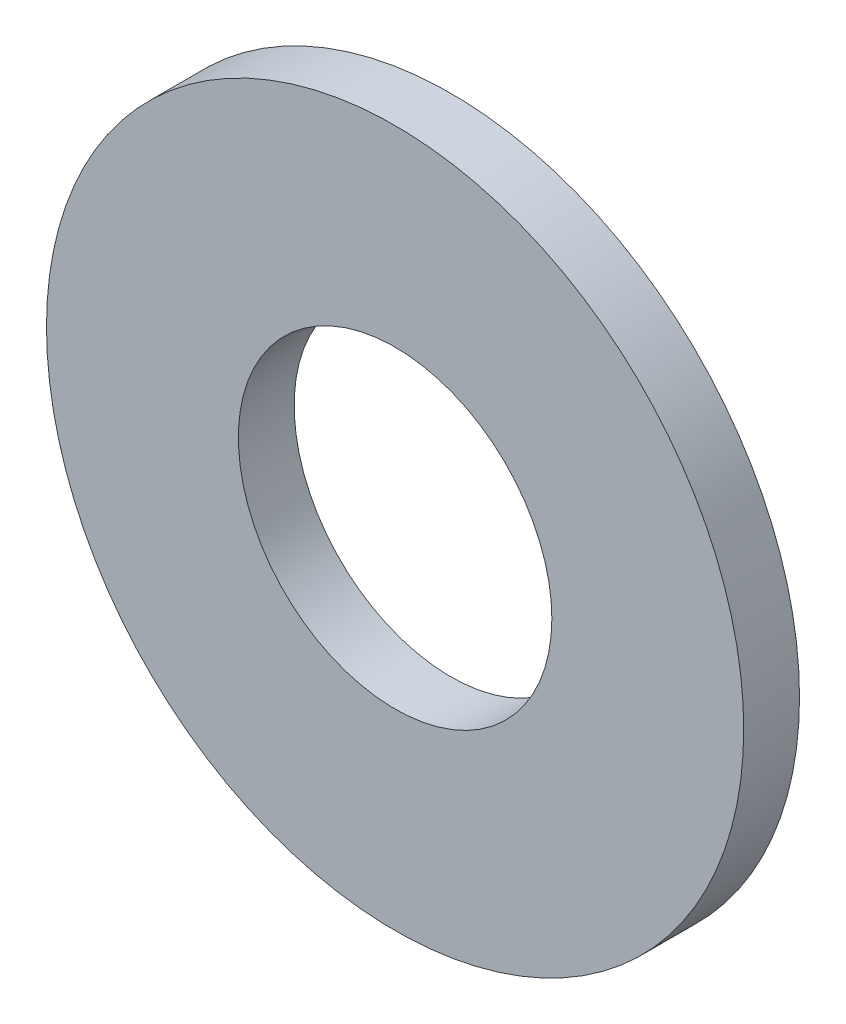
SolidWorks part; units mm, degrees
other "Imported1" parameters "D1"=0.3175, "TH"=1.0287, "Thickness"=1.27
ref_plane "Front Plane" through (0, 0, 0) normal (0, 0, 1) x (1, 0, 0)
ref_plane "Top Plane" through (0, 0, 0) normal (0, 1, 0) x (1, 0, 0)
ref_plane "Right Plane" through (0, 0, 0) normal (1, 0, 0) x (0, 0, -1)
sketch "Sketch1" plane through (0, 0, 0) normal (0, 0, 1) x (1, 0, 0)
  line L0 (-7.9375, 0) -> (7.9375, 0) construction
  line L1 (-3.5687, 0) -> (3.5687, 0) construction
  circle A0 centre (0, 0) radius 3.5687 construction
  circle A1 centre (0, 0) radius 7.9375 construction
  point P8 (0, 0)
  point P9 (0, 7.9375)
  point P11 (3.5687, 0)
  dimension "ID" = 7.1374
  dimension "OD" = 15.875
sketch "Sketch2" plane through (0, 0, 0) normal (1, 0, 0) x (0, 0, -1)
  line L0 (-0.635, 7.9375) -> (0.635, 7.9375) construction
  point P2 (0, 7.9375)
sketch "Sketch3" plane through (0, 0, 0) normal (0, 0, 1) x (1, 0, 0)
  circle A0 centre (0, 0) radius 3.5687
  circle A1 centre (0, 0) radius 7.9375
extrude "Boss-Extrude1" add sketch "Sketch3" along normal up to vertex (0.635 mm away) and the other way up to vertex (0.635 mm away) up to point (0, 7.9375, 0.635) other way up to point (0, 7.9375, -0.635)
fillet "Fillet1" [suppressed] radius 0.3175
equation "\"D1@Fillet1\"=\"Thickness@Sketch2\"/4"
